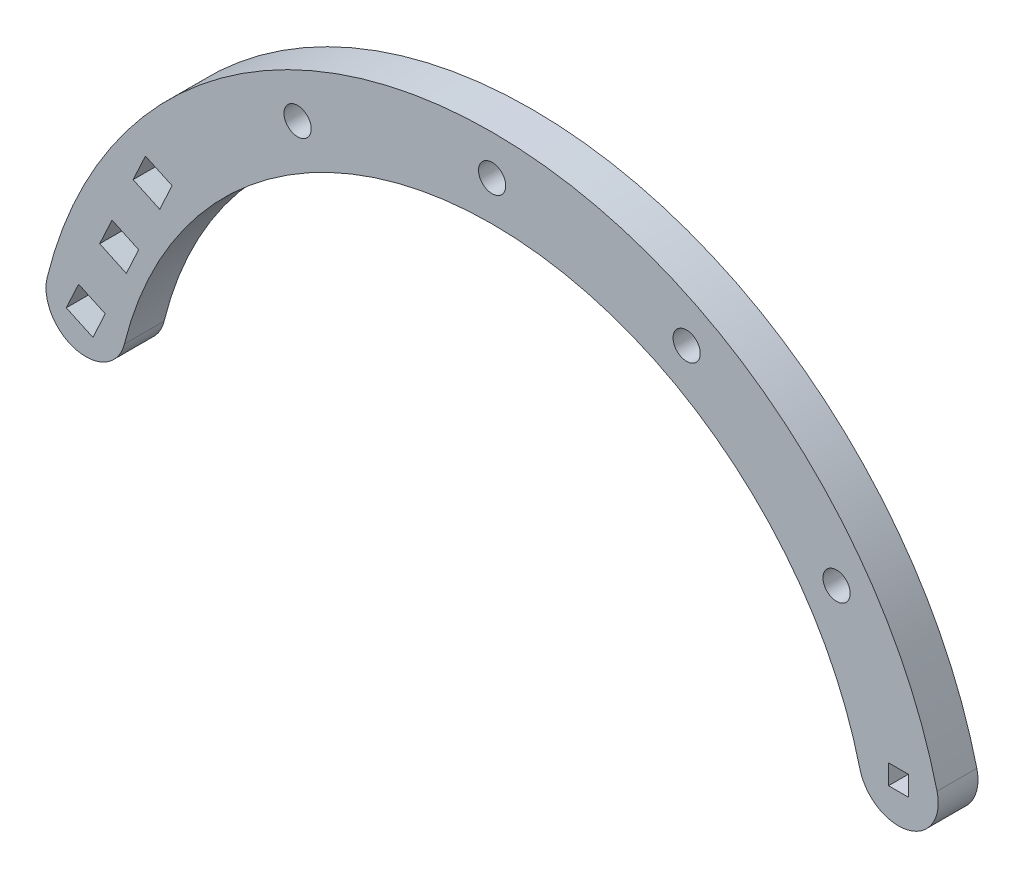
SolidWorks part; units mm, degrees
material "ABS"
ref_plane "Front Plane" through (0, 0, 0) normal (0, 0, 1) x (1, 0, 0)
ref_plane "Top Plane" through (0, 0, 0) normal (0, 1, 0) x (1, 0, 0)
ref_plane "Right Plane" through (0, 0, 0) normal (1, 0, 0) x (0, 0, -1)
sketch "Sketch2" plane through (0, 0, 0) normal (0, 0, 1) x (1, 0, 0)
  line L0 (0, 0) -> (10.6688, 23.0507) construction
  line L1 (-1.1425, 3.1113) -> (3.1113, 1.1425)
  line L2 (128.1811, 1.5875) -> (131.3561, 1.5875)
  line L3 (128.1811, 1.5875) -> (128.1811, -1.5875)
  line L4 (128.1811, -1.5875) -> (131.3561, -1.5875)
  line L5 (131.3561, 1.5875) -> (131.3561, -1.5875)
  line L6 (128.1811, 1.5875) -> (131.3561, -1.5875) construction
  line L7 (128.1811, -1.5875) -> (131.3561, 1.5875) construction
  line L8 (-1.1425, 3.1113) -> (-3.1113, -1.1425)
  line L9 (-3.1113, -1.1425) -> (1.1425, -3.1113)
  line L10 (3.1113, 1.1425) -> (1.1425, -3.1113)
  line L11 (-1.1425, 3.1113) -> (1.1425, -3.1113) construction
  line L12 (-3.1113, -1.1425) -> (3.1113, 1.1425) construction
  line L13 (4.1919, 14.6367) -> (2.2231, 10.3829)
  line L14 (4.1919, 14.6367) -> (8.4458, 12.6679)
  line L15 (8.4458, 12.6679) -> (6.4769, 8.414)
  line L16 (2.2231, 10.3829) -> (6.4769, 8.414)
  line L17 (9.5263, 26.1621) -> (7.5575, 21.9082)
  line L18 (9.5263, 26.1621) -> (13.7802, 24.1932)
  line L19 (13.7802, 24.1932) -> (11.8113, 19.9394)
  line L20 (7.5575, 21.9082) -> (11.8113, 19.9394)
  line L21 (7.5575, 21.9082) -> (13.7802, 24.1932) construction
  line L22 (9.5263, 26.1621) -> (11.8113, 19.9394) construction
  line L23 (2.2231, 10.3829) -> (8.4458, 12.6679) construction
  line L24 (4.1919, 14.6367) -> (6.4769, 8.414) construction
  arc A0 (129.7686, 0) -> (0, 0) centre (64.8843, -16.0367) ccw construction
  arc A1 (135.9331, 1.5236) -> (-6.1645, 1.5236) centre (64.8843, -16.0367) ccw
  arc A2 (123.6041, -1.5236) -> (6.1645, -1.5236) centre (64.8843, -16.0367) ccw
  arc A3 (123.6041, -1.5236) -> (135.9331, 1.5236) centre (129.7686, 0) ccw
  arc A4 (-6.1645, 1.5236) -> (6.1645, -1.5236) centre (0, 0) ccw
  circle A5 centre (0, 0) radius 2.2951 construction
  circle A6 centre (129.7686, 0) radius 2.5 construction
  point P0 (0, 0)
  point P1 (129.7686, 0)
  point P7 (64.8843, 50.8)
  point P23 (5.3344, 11.5254)
  point P24 (10.6688, 23.0507)
  dimension "D3" = 4.5901
  dimension "D4" = 5
  dimension "D1" = 129.7686
  dimension "D2" = 6.35
  dimension "D5" = 3.175
  dimension "D6" = 50.8
  dimension "D7" = 25.4
  dimension "D8" = 4.6874
  dimension "D10" = 12.7
  dimension "D9" = 12.7
extrude "Boss-Extrude1" add sketch "Sketch2" along normal blind 6.35
sketch "Sketch4" plane through (0, 0, 6.35) normal (0, 0, 1) x (1, 0, 0)
  point P0 (64.8843, 50.8)
sketch "Sketch5" plane through (0, 0, 0) normal (0, 0, -1) x (-1, 0, 0)
  circle A0 centre (-64.8843, 50.8) radius 2.1717
  circle A1 centre (-33.8237, 43.1443) radius 2.1717
  circle A2 centre (-9.8787, 21.9309) radius 2.1717
  circle A3 centre (1.4651, -7.9805) radius 2.1717
  circle A4 centre (-2.3909, -39.7374) radius 2.1717
  circle A5 centre (-20.5633, -66.0648) radius 2.1717
  circle A6 centre (-48.8892, -80.9313) radius 2.1717
  circle A7 centre (-80.8794, -80.9313) radius 2.1717
  circle A8 centre (-109.2053, -66.0648) radius 2.1717
  circle A9 centre (-127.3777, -39.7374) radius 2.1717
  circle A10 centre (-131.2337, -7.9805) radius 2.1717
  circle A11 centre (-119.8899, 21.9309) radius 2.1717
  circle A12 centre (-95.9449, 43.1443) radius 2.1717
  dimension "D1" = 4.3434
  dimension "D2" = 13
extrude "Cut-Extrude1" cut sketch "Sketch5" against normal blind 25.4 contours A11 | A0 | A12 | A1
